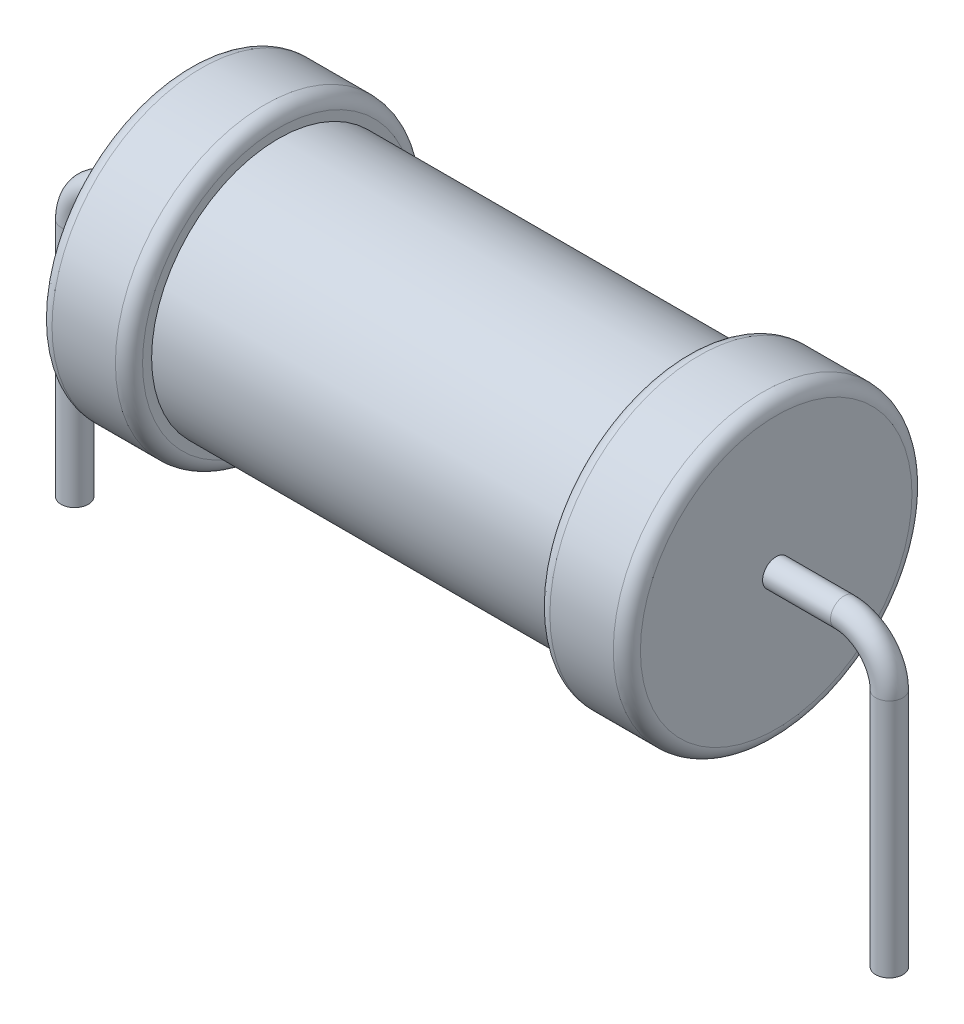
SolidWorks part; units mm, degrees
ref_plane "Спереди" through (0, 0, 0) normal (0, 0, 1) x (1, 0, 0)
ref_plane "Сверху" through (0, 0, 0) normal (0, 1, 0) x (1, 0, 0)
ref_plane "Справа" through (0, 0, 0) normal (1, 0, 0) x (0, 0, -1)
sketch "Эскиз1" plane through (0, 0, 0) normal (0, 0, 1) x (1, 0, 0)
  line L0 (0, 0) -> (101.4955, 0) construction
  line L1 (0, 0) -> (0, 3.3)
  line L2 (0, 3.3) -> (2, 3.3)
  line L3 (2, 3.3) -> (2, 2.8)
  line L4 (2, 2.8) -> (11, 2.8)
  line L5 (11, 2.8) -> (11, 3.3)
  line L6 (11, 3.3) -> (13, 3.3)
  line L7 (13, 3.3) -> (13, 0)
  line L8 (13, 0) -> (0, 0)
  dimension "D1" = 3.3
  dimension "D2" = 13
  dimension "D3" = 2
  dimension "D4" = 0.5
revolve "Повернуть1" add sketch "Эскиз1" angle 360 about L0
sketch "Эскиз2" plane through (0, 0, 0) normal (0, 0, 1) x (1, 0, 0)
  line L0 (-1.5, 0) -> (14.5, 0)
  line L1 (-2.5, -1) -> (-2.5, -6.3)
  line L2 (6.5, 2.8) -> (6.5, -2.8) construction
  line L3 (11, 2.8) -> (2, 2.8) construction
  line L4 (2, -2.8) -> (11, -2.8) construction
  line L5 (15.5, -1) -> (15.5, -6.3)
  line L7 (0, -3.3) -> (2, -3.3) construction
  arc A0 (-1.5, 0) -> (-2.5, -1) centre (-1.5, -1) ccw
  arc A1 (14.5, 0) -> (15.5, -1) centre (14.5, -1) cw
  dimension "D1" = 1
  dimension "D2" = 18
  dimension "D3" = 3
ref_plane "Плоскость1" through (-2.5, -6.3, 0) normal (0, 1, 0) x (-1, 0, 0)
sketch "Эскиз3" plane through (-2.5, -6.3, 0) normal (0, 1, 0) x (-1, 0, 0)
  line L0 (0, 0) -> (-1, 0) construction
  circle A0 centre (0, 0) radius 0.3
  dimension "D1" = 0.6
sweep "По траектории1" add profiles "Эскиз3" path "Эскиз2"
fillet "Скругление1" radius 0.3 4 edges at (13, 0, 3.3) (11, 0, 3.3) (2, 0, 3.3) (0, 0, 3.3)
